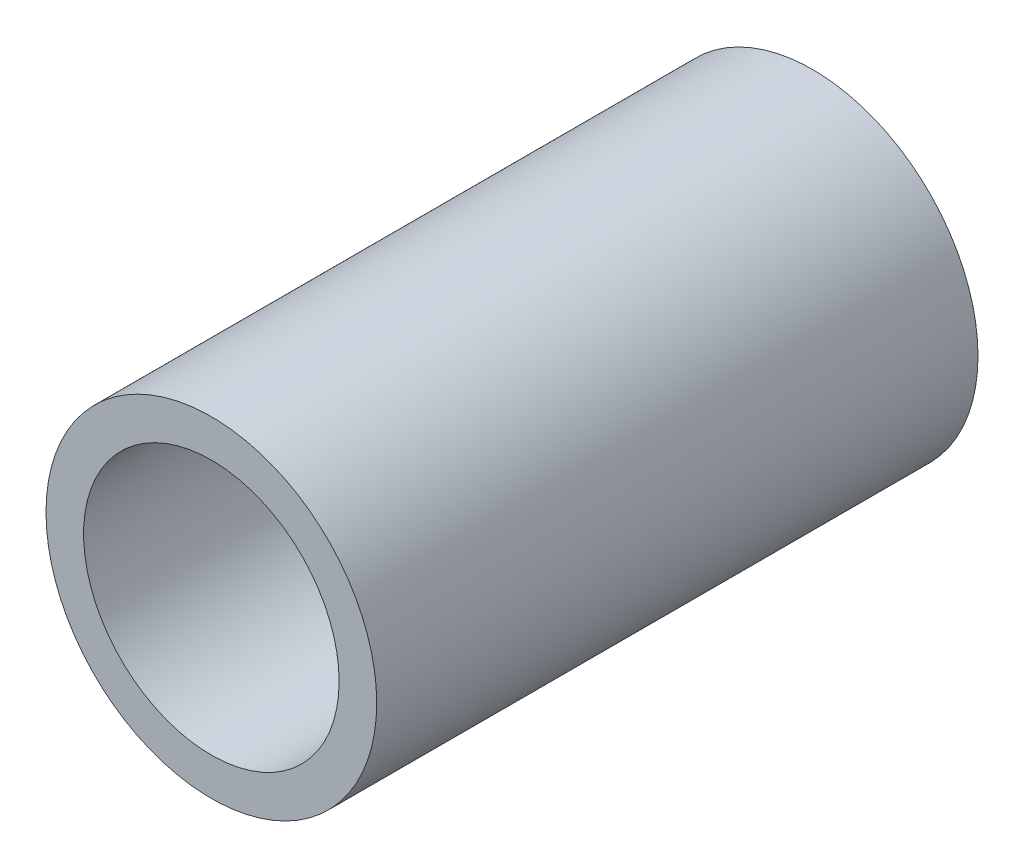
SolidWorks part; units mm, degrees
material "PVC 0.007 Plasticized"
ref_plane "Front Plane" through (0, 0, 0) normal (0, 0, 1) x (1, 0, 0)
ref_plane "Top Plane" through (0, 0, 0) normal (0, 1, 0) x (1, 0, 0)
ref_plane "Right Plane" through (0, 0, 0) normal (1, 0, 0) x (0, 0, -1)
sketch "Sketch1" plane through (0, 0, 0) normal (0, 0, 1) x (1, 0, 0)
  circle A0 centre (0, 0) radius 11
  circle A1 centre (0, 0) radius 8.5
  dimension "D1" = 2.5
extrude "Boss-Extrude1" add sketch "Sketch1" along normal blind 40
